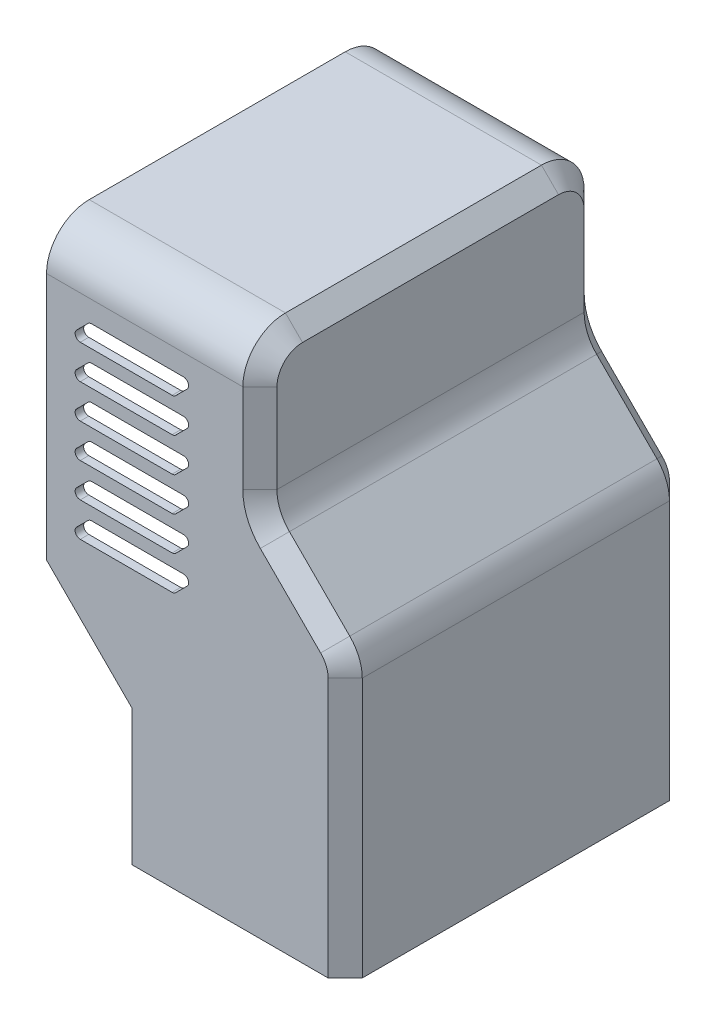
SolidWorks part; units mm, degrees
ref_plane "Front Plane" through (0, 0, 0) normal (0, 0, 1) x (1, 0, 0)
ref_plane "Top Plane" through (0, 0, 0) normal (0, 1, 0) x (1, 0, 0)
ref_plane "Right Plane" through (0, 0, 0) normal (1, 0, 0) x (0, 0, -1)
sketch "Sketch1" plane through (0, 0, 0) normal (0, 0, 1) x (1, 0, 0)
  line L0 (0, 0) -> (0, 82.55)
  line L1 (0, 82.55) -> (-25.4, 107.95)
  line L2 (-25.4, 107.95) -> (-25.4, 152.4)
  line L3 (-25.4, 152.4) -> (-88.9, 152.4)
  line L4 (-88.9, 152.4) -> (-88.9, 65.8289)
  line L5 (-88.9, 65.8289) -> (-63.5, 40.4289)
  line L6 (-63.5, 40.4289) -> (-63.5, 0)
  line L7 (-63.5, 0) -> (0, 0)
  dimension "D1" = 63.5
  dimension "D2" = 44.45
  dimension "D3" = 69.85
  dimension "D4" = 152.4
  dimension "D5" = 76.2
  dimension "D6" = 45
  dimension "D7" = 63.5
extrude "Boss-Extrude1" add sketch "Sketch1" along normal mid plane 101.6
fillet "Fillet2" radius 12.7 4 edges at (0, 82.55, 0) (-25.4, 107.95, 0) (-57.15, 152.4, -50.8) (-57.15, 152.4, 50.8)
chamfer "Chamfer1" distance 5.08 angle 45 13 edges at (0, 38.6447, 50.8) (0, 38.6447, -50.8) (-0.9667, 82.1496, 50.8) (-0.9667, 82.1496, -50.8) (-12.7, 95.25, 50.8) (-12.7, 95.25, -50.8) (-24.4333, 108.3504, 50.8) (-24.4333, 108.3504, -50.8) (-25.4, 126.4553, 50.8) (-25.4, 126.4553, -50.8) (-25.4, 148.6803, 47.0803) (-25.4, 148.6803, -47.0803) (-25.4, 152.4, 0)
shell "Shell1" thickness 2.54
sketch "Sketch2" plane through (0, 0, 50.8) normal (0, 0, 1) x (1, 0, 0)
  line L0 (-75.4815, 133.4373) -> (-48.1293, 133.4373)
  line L1 (-76.5591, 132.9909) -> (-79.9484, 129.6016)
  line L2 (-47.0516, 130.8356) -> (-50.4409, 127.4464)
  line L3 (-78.8707, 127) -> (-51.5185, 127)
  line L4 (-88.9, 152.4) -> (-88.9, 139.7) construction
  line L5 (-75.4815, 123.2773) -> (-48.1293, 123.2773)
  line L6 (-76.5591, 122.8309) -> (-79.9484, 119.4416)
  line L7 (-47.0516, 120.6756) -> (-50.4409, 117.2864)
  line L8 (-78.8707, 116.84) -> (-51.5185, 116.84)
  line L9 (-75.4815, 113.1173) -> (-48.1293, 113.1173)
  line L10 (-76.5591, 112.6709) -> (-79.9484, 109.2816)
  line L11 (-47.0516, 110.5156) -> (-50.4409, 107.1264)
  line L12 (-78.8707, 106.68) -> (-51.5185, 106.68)
  line L13 (-75.4815, 102.9573) -> (-48.1293, 102.9573)
  line L14 (-76.5591, 102.5109) -> (-79.9484, 99.1216)
  line L15 (-47.0516, 100.3556) -> (-50.4409, 96.9664)
  line L16 (-78.8707, 96.52) -> (-51.5185, 96.52)
  line L17 (-75.4815, 92.7973) -> (-48.1293, 92.7973)
  line L18 (-76.5591, 92.3509) -> (-79.9484, 88.9616)
  line L19 (-47.0516, 90.1956) -> (-50.4409, 86.8064)
  line L20 (-78.8707, 86.36) -> (-51.5185, 86.36)
  line L21 (-75.4815, 82.6373) -> (-48.1293, 82.6373)
  line L22 (-76.5591, 82.1909) -> (-79.9484, 78.8016)
  line L23 (-47.0516, 80.0356) -> (-50.4409, 76.6464)
  line L24 (-78.8707, 76.2) -> (-51.5185, 76.2)
  arc A0 (-50.4409, 127.4464) -> (-51.5185, 127) centre (-51.5185, 128.524) cw
  arc A1 (-48.1293, 133.4373) -> (-47.0516, 130.8356) centre (-48.1293, 131.9133) cw
  arc A2 (-76.5591, 132.9909) -> (-75.4815, 133.4373) centre (-75.4815, 131.9133) cw
  arc A3 (-79.9484, 129.6016) -> (-78.8707, 127) centre (-78.8707, 128.524) ccw
  arc A4 (-50.4409, 117.2864) -> (-51.5185, 116.84) centre (-51.5185, 118.364) cw
  arc A5 (-48.1293, 123.2773) -> (-47.0516, 120.6756) centre (-48.1293, 121.7533) cw
  arc A6 (-76.5591, 122.8309) -> (-75.4815, 123.2773) centre (-75.4815, 121.7533) cw
  arc A7 (-79.9484, 119.4416) -> (-78.8707, 116.84) centre (-78.8707, 118.364) ccw
  arc A8 (-50.4409, 107.1264) -> (-51.5185, 106.68) centre (-51.5185, 108.204) cw
  arc A9 (-48.1293, 113.1173) -> (-47.0516, 110.5156) centre (-48.1293, 111.5933) cw
  arc A10 (-76.5591, 112.6709) -> (-75.4815, 113.1173) centre (-75.4815, 111.5933) cw
  arc A11 (-79.9484, 109.2816) -> (-78.8707, 106.68) centre (-78.8707, 108.204) ccw
  arc A12 (-50.4409, 96.9664) -> (-51.5185, 96.52) centre (-51.5185, 98.044) cw
  arc A13 (-48.1293, 102.9573) -> (-47.0516, 100.3556) centre (-48.1293, 101.4333) cw
  arc A14 (-76.5591, 102.5109) -> (-75.4815, 102.9573) centre (-75.4815, 101.4333) cw
  arc A15 (-79.9484, 99.1216) -> (-78.8707, 96.52) centre (-78.8707, 98.044) ccw
  arc A16 (-50.4409, 86.8064) -> (-51.5185, 86.36) centre (-51.5185, 87.884) cw
  arc A17 (-48.1293, 92.7973) -> (-47.0516, 90.1956) centre (-48.1293, 91.2733) cw
  arc A18 (-76.5591, 92.3509) -> (-75.4815, 92.7973) centre (-75.4815, 91.2733) cw
  arc A19 (-79.9484, 88.9616) -> (-78.8707, 86.36) centre (-78.8707, 87.884) ccw
  arc A20 (-50.4409, 76.6464) -> (-51.5185, 76.2) centre (-51.5185, 77.724) cw
  arc A21 (-48.1293, 82.6373) -> (-47.0516, 80.0356) centre (-48.1293, 81.1133) cw
  arc A22 (-76.5591, 82.1909) -> (-75.4815, 82.6373) centre (-75.4815, 81.1133) cw
  arc A23 (-79.9484, 78.8016) -> (-78.8707, 76.2) centre (-78.8707, 77.724) ccw
  point P13 (-44.45, 133.4373)
  point P16 (-76.1127, 133.4373)
  point P19 (-82.55, 127)
  dimension "D6" = 1.524
  dimension "D1" = 6.35
  dimension "D2" = 25.4
  dimension "D3" = 45
  dimension "D4" = 6.4373
  dimension "D5" = 38.1
  dimension "D7" = 6
extrude "Cut-Extrude1" cut sketch "Sketch2" against normal through all
